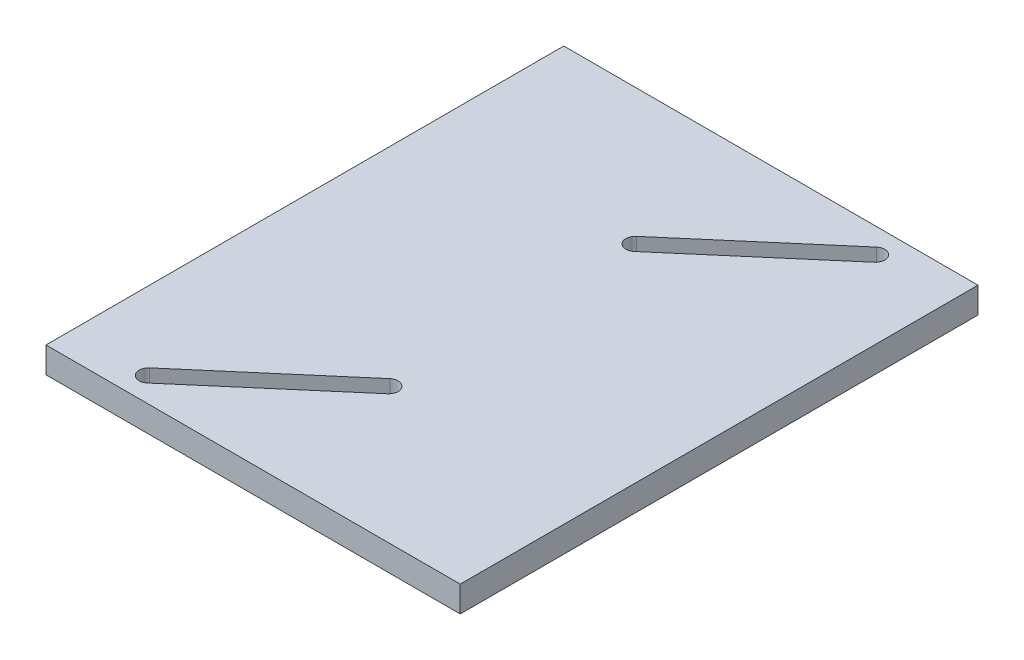
SolidWorks part; units mm, degrees
ref_plane "Front Plane" through (0, 0, 0) normal (0, 0, 1) x (1, 0, 0)
ref_plane "Top Plane" through (0, 0, 0) normal (0, 1, 0) x (1, 0, 0)
ref_plane "Right Plane" through (0, 0, 0) normal (1, 0, 0) x (0, 0, -1)
sketch "Sketch1" plane through (0, 0, 0) normal (0, 1, 0) x (1, 0, 0)
  line L1 (-50.8, -63.5) -> (50.8, -63.5)
  line L2 (-50.8, -63.5) -> (-50.8, 63.5)
  line L3 (-50.8, 63.5) -> (50.8, 63.5)
  line L4 (50.8, -63.5) -> (50.8, 63.5)
  dimension "D1" = 101.6
  dimension "D2" = 127
  dimension "D3" = 50.8
  dimension "D4" = 63.5
extrude "Boss-Extrude1" add sketch "Sketch1" along normal blind 6.35
sketch "Sketch3" plane through (0, 6.35, 0) normal (0, 1, 0) x (1, 0, 0)
  line L0 (0, -63.5) -> (0, 63.5) construction
  line L1 (-50.8, -63.5) -> (50.8, -63.5) construction
  line L2 (50.8, 63.5) -> (-50.8, 63.5) construction
  line L3 (0, 30.226) -> (31.75, 57.404) construction
  line L4 (50.8, -63.5) -> (50.8, 63.5) construction
  line L5 (50.8, 0) -> (-50.8, 0) construction
  line L6 (-50.8, 63.5) -> (-50.8, -63.5) construction
  line L7 (-1.4866, 31.9626) -> (30.2634, 59.1406)
  line L8 (1.4866, 28.4894) -> (33.2366, 55.6674)
  line L9 (0, -30.226) -> (-31.75, -57.404) construction
  line L10 (1.4866, -31.9626) -> (-30.2634, -59.1406)
  line L11 (-1.4866, -28.4894) -> (-33.2366, -55.6674)
  arc A0 (-1.4866, 31.9626) -> (1.4866, 28.4894) centre (0, 30.226) ccw
  arc A1 (33.2366, 55.6674) -> (30.2634, 59.1406) centre (31.75, 57.404) ccw
  arc A2 (1.4866, -31.9626) -> (-1.4866, -28.4894) centre (0, -30.226) ccw
  arc A3 (-33.2366, -55.6674) -> (-30.2634, -59.1406) centre (-31.75, -57.404) ccw
  point P15 (15.875, 43.815)
  point P24 (-15.875, -43.815)
  point P29 (0, 0)
  dimension "D1" = 30.226
  dimension "D2" = 27.178
  dimension "D3" = 31.75
  dimension "D4" = 4.572
  dimension "D5" = 2
extrude "Cut-Extrude1" cut sketch "Sketch3" against normal through all
